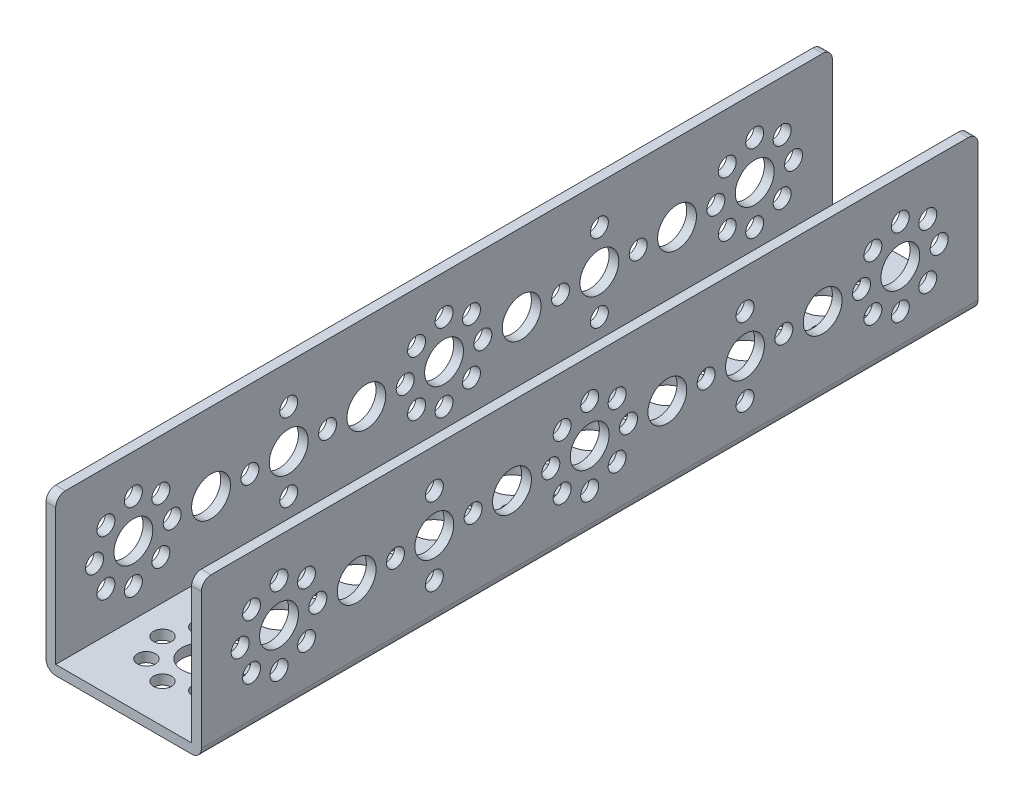
SolidWorks part; units mm, degrees
other "Defeature"
material "5052 Alloy"
ref_plane "Front Plane" through (0, 0, 0) normal (0, 0, 1) x (1, 0, 0)
ref_plane "Top Plane" through (0, 0, 0) normal (0, 1, 0) x (1, 0, 0)
ref_plane "Right Plane" through (0, 0, 0) normal (1, 0, 0) x (0, 0, -1)
sketch "Sketch1" plane through (0, 0, 0) normal (0, 0, 1) x (1, 0, 0)
  line L0 (-14, 0) -> (14, 0)
  line L1 (16, 2) -> (16, 32)
  line L2 (16, 32) -> (14, 32)
  line L3 (14, 32) -> (14, 2)
  line L4 (14, 2) -> (-14, 2)
  line L5 (-14, 2) -> (-14, 32)
  line L6 (-14, 32) -> (-16, 32)
  line L7 (-16, 32) -> (-16, 2)
  arc A0 (-16, 2) -> (-14, 0) centre (-14, 2) ccw
  arc A1 (16, 2) -> (14, 0) centre (14, 2) cw
  point P11 (0, 0)
  point P14 (16, 0)
  dimension "D6" = 2
  dimension "D1" = 32
  dimension "D2" = 2
  dimension "D3" = 2
  dimension "D4" = 32
  dimension "D5" = 2
extrude "Boss-Extrude1" add sketch "Sketch1" against normal mid plane 160
sketch "Sketch2" plane through (16, 0, 0) normal (1, 0, 0) x (0, 0, -1)
  line L1 (80, 32) -> (-80, 32) construction
  point P5 (0, 32)
  circle B0 centre (-32, 16) radius 4
  circle B1 centre (-24, 16) radius 1.85
  circle B2 centre (-40, 16) radius 1.85
  circle B3 centre (-32, 8) radius 1.85
  circle B4 centre (-32, 24) radius 1.85
  circle B5 centre (-48, 16) radius 4
  circle B6 centre (-16, 16) radius 4
  circle B7 centre (16, 16) radius 4
  circle B8 centre (48, 16) radius 4
  circle B9 centre (-58.3431, 21.6569) radius 1.85
  circle B10 centre (-64, 24) radius 1.85
  circle B11 centre (-69.6569, 21.6569) radius 1.85
  circle B12 centre (-64, 16) radius 4
  circle B13 centre (-56, 16) radius 1.85
  circle B14 centre (-72, 16) radius 1.85
  circle B15 centre (-64, 8) radius 1.85
  circle B16 centre (-58.3431, 10.3431) radius 1.85
  circle B17 centre (-69.6569, 10.3431) radius 1.85
  circle B18 centre (32, 16) radius 4
  circle B19 centre (40, 16) radius 1.85
  circle B20 centre (24, 16) radius 1.85
  circle B21 centre (32, 8) radius 1.85
  circle B22 centre (32, 24) radius 1.85
  circle B23 centre (64, 16) radius 4
  circle B24 centre (72, 16) radius 1.85
  circle B25 centre (56, 16) radius 1.85
  circle B26 centre (64, 8) radius 1.85
  circle B27 centre (64, 24) radius 1.85
  circle B28 centre (58.3431, 21.6569) radius 1.85
  circle B29 centre (69.6569, 21.6569) radius 1.85
  circle B30 centre (69.6569, 10.3431) radius 1.85
  circle B31 centre (58.3431, 10.3431) radius 1.85
  circle B32 centre (0, 16) radius 4
  circle B33 centre (8, 16) radius 1.85
  circle B34 centre (-8, 16) radius 1.85
  circle B35 centre (0, 8) radius 1.85
  circle B36 centre (0, 24) radius 1.85
  circle B37 centre (-5.6569, 21.6569) radius 1.85
  circle B38 centre (5.6569, 21.6569) radius 1.85
  circle B39 centre (5.6569, 10.3431) radius 1.85
  circle B40 centre (-5.6569, 10.3431) radius 1.85
  circle B41 centre (-32, 16) radius 8 construction
  line B42 (-69.6569, 21.6569) -> (-58.3431, 10.3431) construction
  line B43 (-58.3431, 21.6569) -> (-69.6569, 10.3431) construction
  line B44 (-64, 8) -> (-64, 16) construction
  circle B45 centre (-64, 16) radius 8 construction
  dimension "D1" = 16
sketch_block_instance "Block6-1"
sketch_block "Block6" parameters "D9"=8, "D1"=16, "D2"=16, "D3"=16, "D4"=16, "D5"=16, "D6"=16, "D7"=16, "D8"=16
sketch_block_instance "Block5-1"
sketch_block "Block5" parameters "D1"=8, "D2"=3.7, "D3"=16
sketch_block_instance "Block2-4"
sketch_block "Block2" parameters "D1"=3.7, "D2"=8, "D3"=16, "D4"=3.7
sketch_block_instance "Block5-2"
sketch_block_instance "Block2-6"
sketch_block_instance "Block2-5"
extrude "Cut-Extrude1" cut sketch "Sketch2" against normal through all
sketch "Sketch5" plane through (0, 0, 0) normal (0, -1, 0) x (1, 0, 0)
  line L0 (-14, 80) -> (14, 80) construction
  line L1 (-14, -80) -> (14, -80) construction
  line L3 (-14, -80) -> (-14, 80) construction
  point P6 (0, -80)
  point P7 (-14, 0)
  point P8 (0, 80)
  circle B0 centre (0, -32) radius 4
  circle B1 centre (0, -24) radius 1.85
  circle B2 centre (0, -40) radius 1.85
  circle B3 centre (8, -32) radius 1.85
  circle B4 centre (-8, -32) radius 1.85
  circle B5 centre (0, -48) radius 4
  circle B6 centre (0, -16) radius 4
  circle B7 centre (0, 16) radius 4
  circle B8 centre (0, 48) radius 4
  circle B9 centre (-5.6569, -58.3431) radius 1.85
  circle B10 centre (-8, -64) radius 1.85
  circle B11 centre (-5.6569, -69.6569) radius 1.85
  circle B12 centre (0, -64) radius 4
  circle B13 centre (0, -56) radius 1.85
  circle B14 centre (0, -72) radius 1.85
  circle B15 centre (8, -64) radius 1.85
  circle B16 centre (5.6569, -58.3431) radius 1.85
  circle B17 centre (5.6569, -69.6569) radius 1.85
  circle B18 centre (0, 32) radius 4
  circle B19 centre (0, 40) radius 1.85
  circle B20 centre (0, 24) radius 1.85
  circle B21 centre (8, 32) radius 1.85
  circle B22 centre (-8, 32) radius 1.85
  circle B23 centre (0, 64) radius 4
  circle B24 centre (0, 72) radius 1.85
  circle B25 centre (0, 56) radius 1.85
  circle B26 centre (8, 64) radius 1.85
  circle B27 centre (-8, 64) radius 1.85
  circle B28 centre (-5.6569, 58.3431) radius 1.85
  circle B29 centre (-5.6569, 69.6569) radius 1.85
  circle B30 centre (5.6569, 69.6569) radius 1.85
  circle B31 centre (5.6569, 58.3431) radius 1.85
  circle B32 centre (0, 0) radius 4
  circle B33 centre (0, 8) radius 1.85
  circle B34 centre (0, -8) radius 1.85
  circle B35 centre (8, 0) radius 1.85
  circle B36 centre (-8, 0) radius 1.85
  circle B37 centre (-5.6569, -5.6569) radius 1.85
  circle B38 centre (-5.6569, 5.6569) radius 1.85
  circle B39 centre (5.6569, 5.6569) radius 1.85
  circle B40 centre (5.6569, -5.6569) radius 1.85
sketch_block_instance "Block6-3"
extrude "Cut-Extrude2" cut sketch "Sketch5" against normal up to surface (2 mm away) up to face at (0, 2, 0)
fillet "Fillet1" radius 2 4 edges at (15, 32, 80) (15, 32, -80) (-15, 32, -80) (-15, 32, 80)
